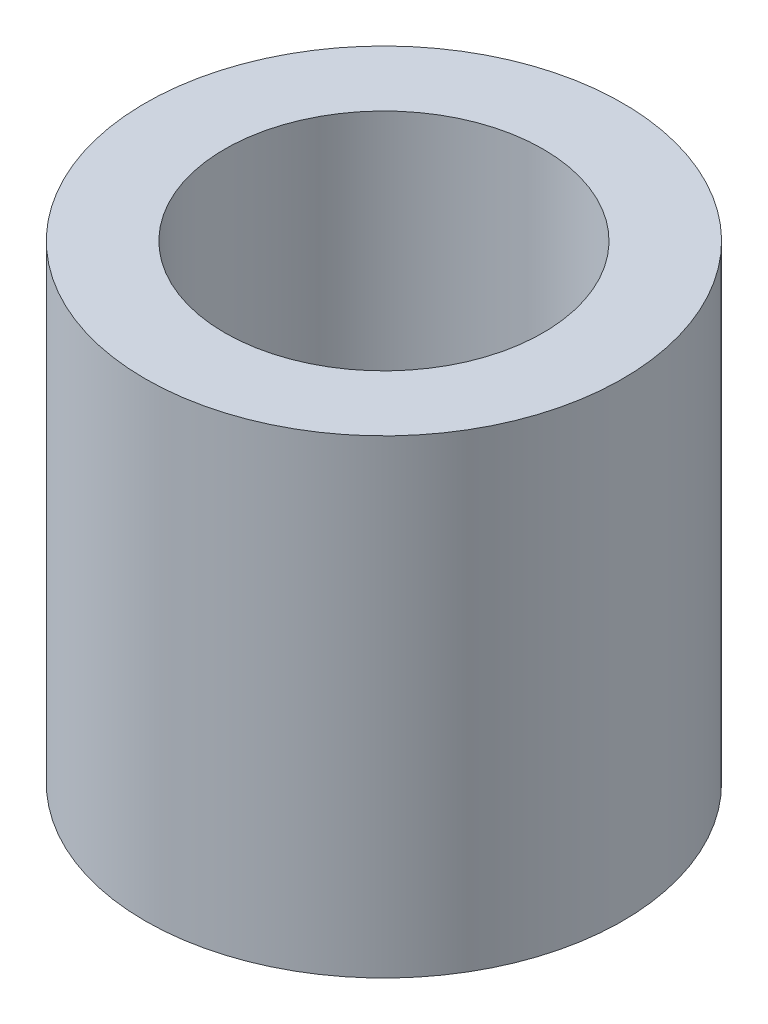
SolidWorks part; units mm, degrees
ref_plane "Front Plane" through (0, 0, 0) normal (0, 0, 1) x (1, 0, 0)
ref_plane "Top Plane" through (0, 0, 0) normal (0, 1, 0) x (1, 0, 0)
ref_plane "Right Plane" through (0, 0, 0) normal (1, 0, 0) x (0, 0, -1)
sketch "Sketch1" plane through (0, 0, 0) normal (0, 1, 0) x (1, 0, 0)
  circle A0 centre (0, 0) radius 7.5
  dimension "D1" = 15
extrude "Boss-Extrude1" add sketch "Sketch1" along normal blind 14.75
sketch "Sketch2" plane through (0, 14.75, 0) normal (0, 1, 0) x (1, 0, 0)
  circle A0 centre (0, 0) radius 5
  dimension "D1" = 10
extrude "Cut-Extrude1" cut sketch "Sketch2" against normal blind 10
